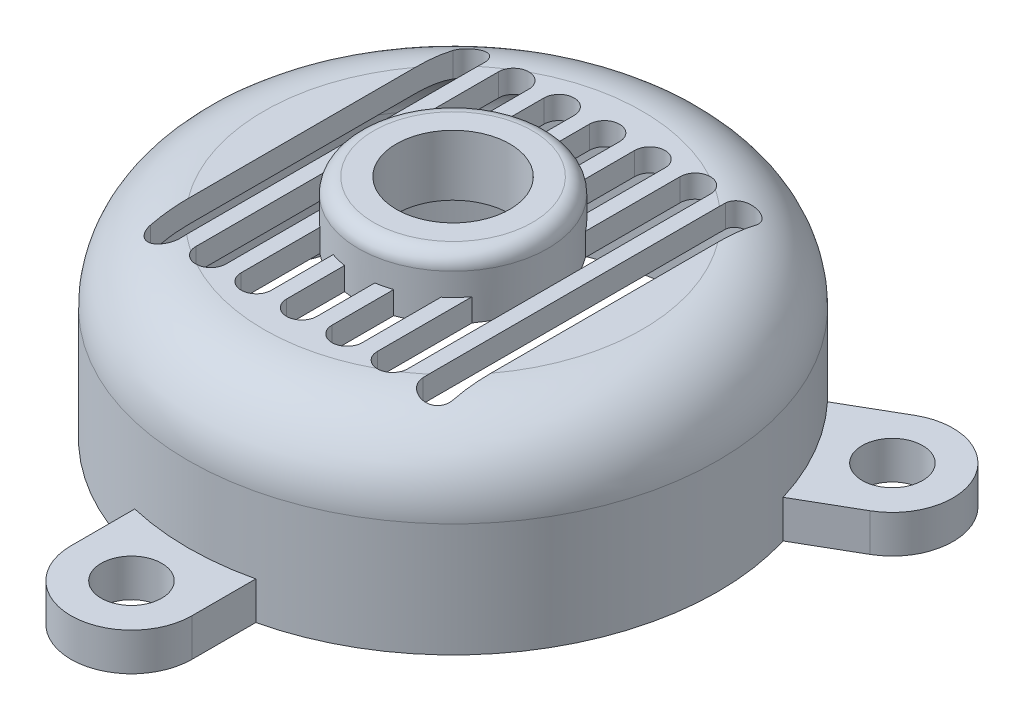
SolidWorks part; units mm, degrees
ref_plane "Front Plane" through (0, 0, 0) normal (0, 0, 1) x (1, 0, 0)
ref_plane "Top Plane" through (0, 0, 0) normal (0, 1, 0) x (1, 0, 0)
ref_plane "Right Plane" through (0, 0, 0) normal (1, 0, 0) x (0, 0, -1)
sketch "Sketch1" plane through (0, 0, 0) normal (0, 1, 0) x (1, 0, 0)
  circle A0 centre (0, 0) radius 35
  dimension "D1" = 70
extrude "Boss-Extrude1" add sketch "Sketch1" along normal blind 25
fillet "Fillet1" radius 10 1 edges at (0, 25, 35)
shell "Shell1" thickness 3
sketch "Sketch2" plane through (0, 0, 0) normal (0, -1, 0) x (1, 0, 0)
  line L1 (-8, 42.5) -> (8, 42.5) construction
  line L2 (-8, 42.5) -> (-8, 32)
  line L3 (-8, 32) -> (8, 32)
  line L4 (8, 42.5) -> (8, 32)
  line L5 (-8, 42.5) -> (8, 32) construction
  line L6 (-8, 32) -> (8, 42.5) construction
  arc A0 (8, 42.5) -> (-8, 42.5) centre (0, 42.5) ccw
  circle A1 centre (0, 42.5) radius 4
  circle A2 centre (0, 0) radius 32 construction
  point P0 (0, 37.25)
  dimension "D1" = 16
  dimension "D2" = 8
  dimension "D3" = 42.5
extrude "Boss-Extrude2" add sketch "Sketch2" against normal blind 5
pattern_circular "CirPattern1" count 3 over 360 about axis through (0, 0, 0) along (0, 1, 0) of "Boss-Extrude2"
sketch "Sketch4" plane through (0, 25, 0) normal (0, 1, 0) x (1, 0, 0)
  line L0 (-18, 20) -> (-18, -20) construction
  line L1 (-16, 20) -> (-16, -20)
  line L2 (-20, 20) -> (-20, -20)
  arc A0 (-16, 20) -> (-20, 20) centre (-18, 20) ccw
  arc A1 (-20, -20) -> (-16, -20) centre (-18, -20) ccw
  point P2 (-18, 0)
  point P7 (-18, -1.4969)
  point P8 (0, 0)
  dimension "D2" = 18
  dimension "D1" = 2
  dimension "D3" = 40
extrude "Cut-Extrude1" cut sketch "Sketch4" against normal through all
sketch "Sketch5" plane through (0, 25, 0) normal (0, 1, 0) x (1, 0, 0)
  line L0 (0, 0) -> (12.7595, 0)
pattern_linear "LPattern1" count 7 spacing 6 along (1, 0, 0) of "Cut-Extrude1"
sketch "Sketch6" plane through (0, 25, 0) normal (0, 1, 0) x (1, 0, 0)
  circle A0 centre (0, 0) radius 12.5
  dimension "D1" = 25
extrude "Boss-Extrude3" add sketch "Sketch6" along normal blind 5 and the other way blind 3
fillet "Fillet2" radius 2 1 edges at (0, 30, 12.5)
sketch "Sketch7" plane through (0, 30, 0) normal (0, 1, 0) x (1, 0, 0)
  circle A0 centre (0, 0) radius 7.5
  dimension "D1" = 15
extrude "Cut-Extrude2" cut sketch "Sketch7" against normal through all
